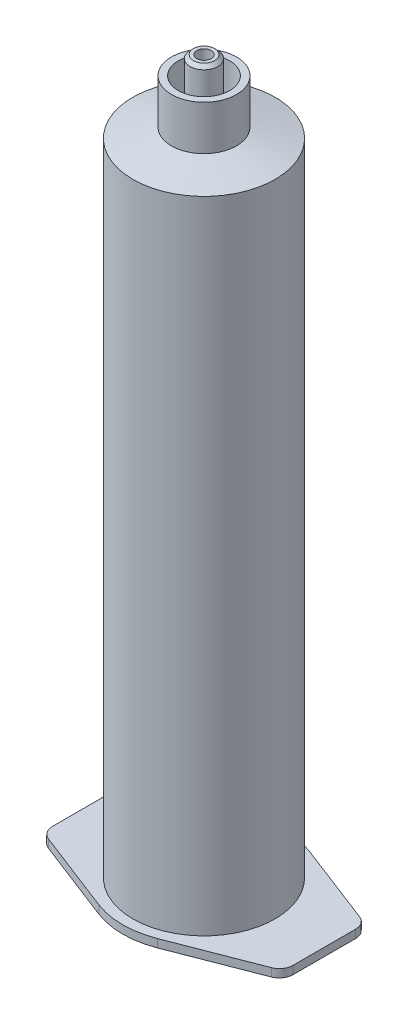
SolidWorks part; units mm, degrees
ref_plane "Спереди" through (0, 0, 0) normal (0, 0, 1) x (1, 0, 0)
ref_plane "Сверху" through (0, 0, 0) normal (0, 1, 0) x (1, 0, 0)
ref_plane "Справа" through (0, 0, 0) normal (1, 0, 0) x (0, 0, -1)
sketch "Эскиз1" plane through (0, 0, 0) normal (0, 0, 1) x (1, 0, 0)
  line L0 (0, 0) -> (0, -70.8222) construction
  line L1 (1.05, 5.5706) -> (1.55, 5.5706)
  line L2 (2.05, 5.0706) -> (2.05, -3.0087)
  line L3 (2.05, -3.0087) -> (3.8, -3.4479)
  line L4 (10.5, -5.1294) -> (10.5, -99.6294)
  line L5 (3.8, -3.4479) -> (3.8, 2.8706)
  line L6 (3.8, 2.8706) -> (4.8, 2.8706)
  line L7 (4.8, 2.8706) -> (4.8, -3.6988)
  line L8 (4.8, -3.6988) -> (10.5, -5.1294)
  line L9 (1.05, 5.5706) -> (1.05, -3.7887)
  line L10 (1.05, -3.7887) -> (9.5, -5.9094)
  line L11 (9.5, -5.9094) -> (9.5, -99.6294)
  line L12 (9.5, -99.6294) -> (10.5, -99.6294)
  line L13 (1.55, 5.5706) -> (2.05, 5.0706)
  point P4 (2.05, 5.5706)
  dimension "D1" = 4.1
  dimension "D2" = 1
  dimension "D3" = 9.6
  dimension "D4" = 1
  dimension "D5" = 1
  dimension "D6" = 105.2
  dimension "D7" = 1
  dimension "D8" = 21
  dimension "D9" = 94.5
  dimension "D10" = 2.7
  dimension "D12" = 104.088
revolve "Повернуть1" add sketch "Эскиз1" angle 360 about L0
sketch "Эскиз2" plane through (0, -99.6294, 0) normal (0, -1, 0) x (1, 0, 0)
  line L0 (16.4716, -6.4946) -> (4.3296, -11.1917)
  line L2 (17.75, 4.6293) -> (17.75, -4.6293)
  line L4 (-17.75, 4.6293) -> (-17.75, -4.6293)
  line L5 (17.75, 6) -> (-17.75, -6) construction
  line L6 (17.75, -6) -> (-17.75, 6) construction
  line L7 (-16.4716, -6.4946) -> (-4.3296, -11.1917)
  line L8 (-16.4716, 6.4946) -> (-4.3296, 11.1917)
  line L9 (16.4716, 6.4946) -> (4.3296, 11.1917)
  circle A0 centre (0, 0) radius 9.5 construction
  circle A1 centre (0, 0) radius 9.5
  arc A2 (4.3296, 11.1917) -> (-4.3296, 11.1917) centre (0, 0) ccw
  arc A3 (-4.3296, -11.1917) -> (4.3296, -11.1917) centre (0, 0) ccw
  arc A4 (-17.75, -4.6293) -> (-16.4716, -6.4946) centre (-15.75, -4.6293) ccw
  arc A5 (-17.75, 4.6293) -> (-16.4716, 6.4946) centre (-15.75, 4.6293) cw
  arc A6 (16.4716, 6.4946) -> (17.75, 4.6293) centre (15.75, 4.6293) cw
  arc A7 (16.4716, -6.4946) -> (17.75, -4.6293) centre (15.75, -4.6293) ccw
  dimension "D1" = 24
  dimension "D4" = 2
  dimension "D2" = 35.5
  dimension "D3" = 12
extrude "Бобышка-Вытянуть1" add sketch "Эскиз2" along normal blind 1.2
